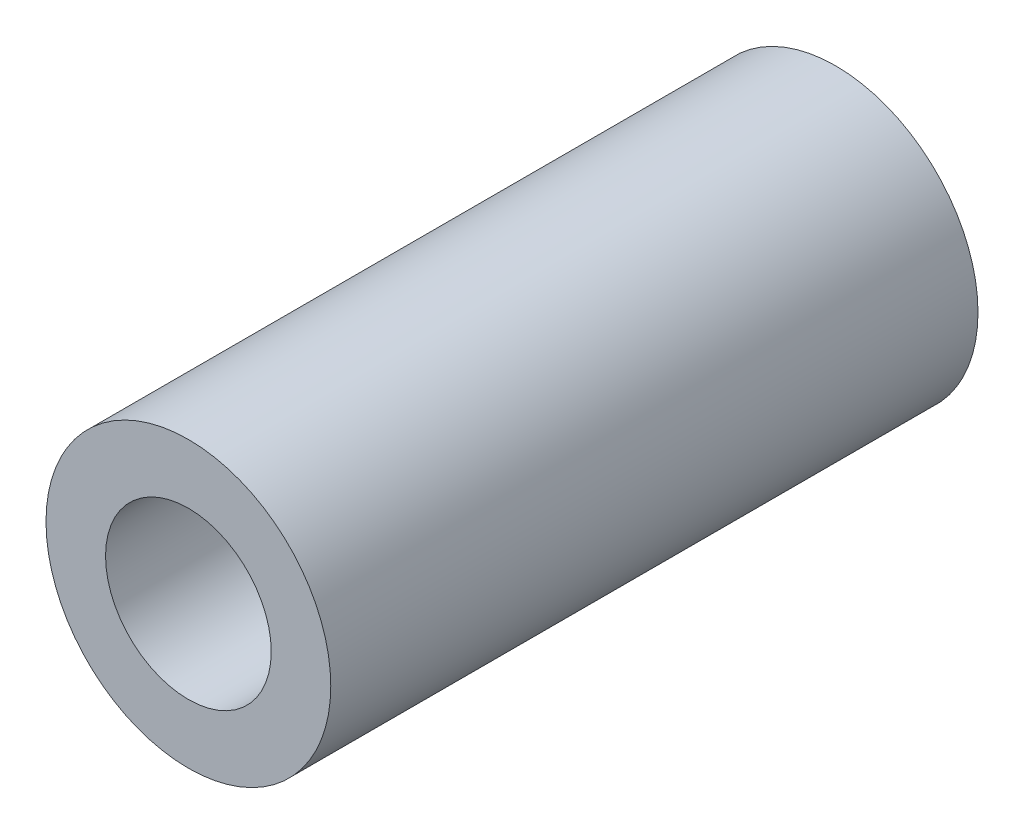
SolidWorks part; units mm, degrees
material "ABS"
ref_plane "正面" through (0, 0, 0) normal (0, 0, 1) x (1, 0, 0)
ref_plane "平面" through (0, 0, 0) normal (0, 1, 0) x (1, 0, 0)
ref_plane "右側面" through (0, 0, 0) normal (1, 0, 0) x (0, 0, -1)
sketch "ｽｹｯﾁ1" plane through (0, 0, 0) normal (0, 0, 1) x (1, 0, 0)
  circle A0 centre (0, 0) radius 1.6
  circle A1 centre (0, 0) radius 2.75
  dimension "D1" = 3.2
  dimension "D2" = 5.5
extrude "ﾎﾞｽ - 押し出し1" add sketch "ｽｹｯﾁ1" along normal blind 12.5
